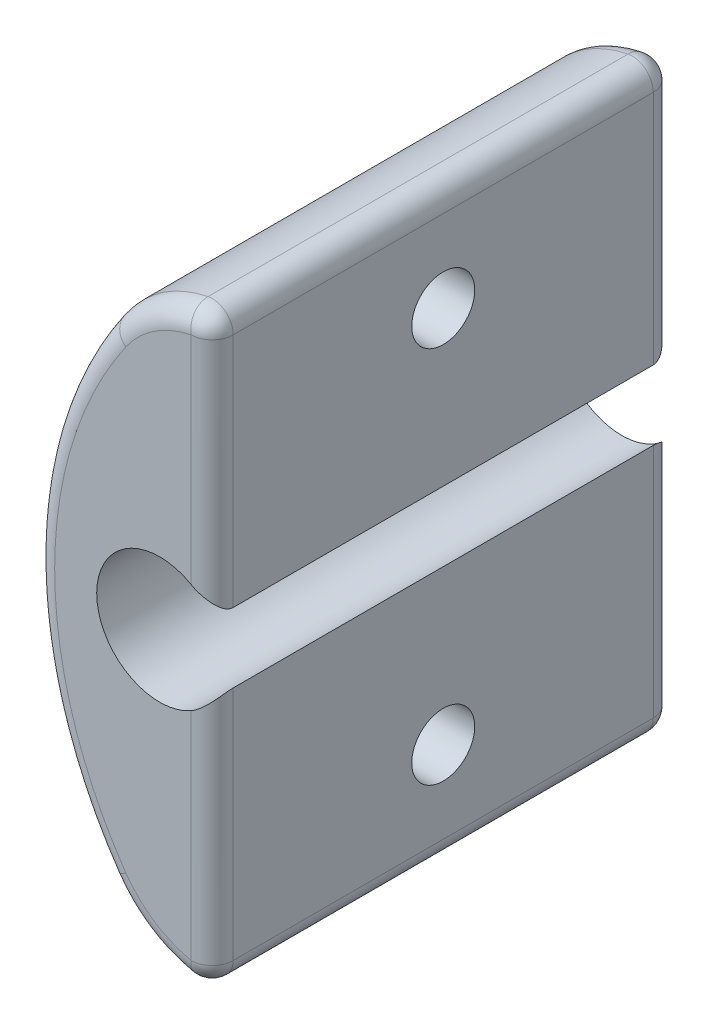
SolidWorks part; units mm, degrees
material "ABS"
ref_plane "Front" through (0, 0, 0) normal (0, 0, 1) x (1, 0, 0)
ref_plane "Top" through (0, 0, 0) normal (0, 1, 0) x (1, 0, 0)
ref_plane "Right" through (0, 0, 0) normal (1, 0, 0) x (0, 0, -1)
sketch "Esquisse1" plane through (0, 0, 0) normal (0, 0, 1) x (1, 0, 0)
  line L0 (-3, 0) -> (-6, 0)
  line L1 (2.5, 14) -> (2.5, 1.6583)
  arc A0 (2.5, 1.6583) -> (-3, 0) centre (0, 0) ccw
  arc A1 (-6, 0) -> (-2.4324, 11.4164) centre (14.05, 0) cw
  arc A2 (-2.4324, 11.4164) -> (2.5, 14) centre (2.5, 8) cw
  dimension "D1" = 3
  dimension "D5" = 6
  dimension "D2" = 2.5
  dimension "D3" = 6
  dimension "D4" = 14
extrude "Boss.-Extru.1" add sketch "Esquisse1" along normal mid plane 22
sketch "Esquisse2" plane through (0, 0, 0) normal (0, 0, 1) x (1, 0, 0)
  line L0 (2.5, 1.6583) -> (2.5, 14) construction
  line L1 (2.5, 7.5) -> (-1.5, 7.5)
  line L2 (2.5, 7.5) -> (2.5, 9)
  line L3 (2.5, 9) -> (-5.0812, 9)
  line L4 (-5.0812, 6) -> (-5.0812, 9)
  line L5 (-5.0812, 9) -> (-8.6624, 9) construction
  line L8 (-5.0812, 6) -> (-1.5, 6)
  line L9 (-1.5, 7.5) -> (-1.5, 6)
  arc A0 (-2.4324, 11.4164) -> (-6, 0) centre (14.05, 0) ccw construction
  dimension "D1" = 3
  dimension "D2" = 6
  dimension "D3" = 9
  dimension "D4" = 4
  dimension "D5" = 3.5812
revolve "Enlèvement de matière-Révolution1" cut sketch "Esquisse2" angle 360 about L5
fillet "Congé1" radius 1 7 edges at (-5.0873, 5.9804, 11) (-5.0873, 5.9804, -11) (2.5, 14, 0) (2.5, 7.8292, -11) (2.5, 7.8292, 11) (-0.284, 13.315, 11) (-0.284, 13.315, -11)
mirror "Symétrie1" about plane through (-3, 0, 11) normal (0, 1, 0) of bodies 102 104
sketch "Esquisse4" plane through (0, 0, 11) normal (0, 0, 1) x (1, 0, 0)
  circle A0 centre (0, 0) radius 25.4407
extrude "Boss.-Extru.3" [suppressed] add sketch "Esquisse4" against normal blind 0.2
